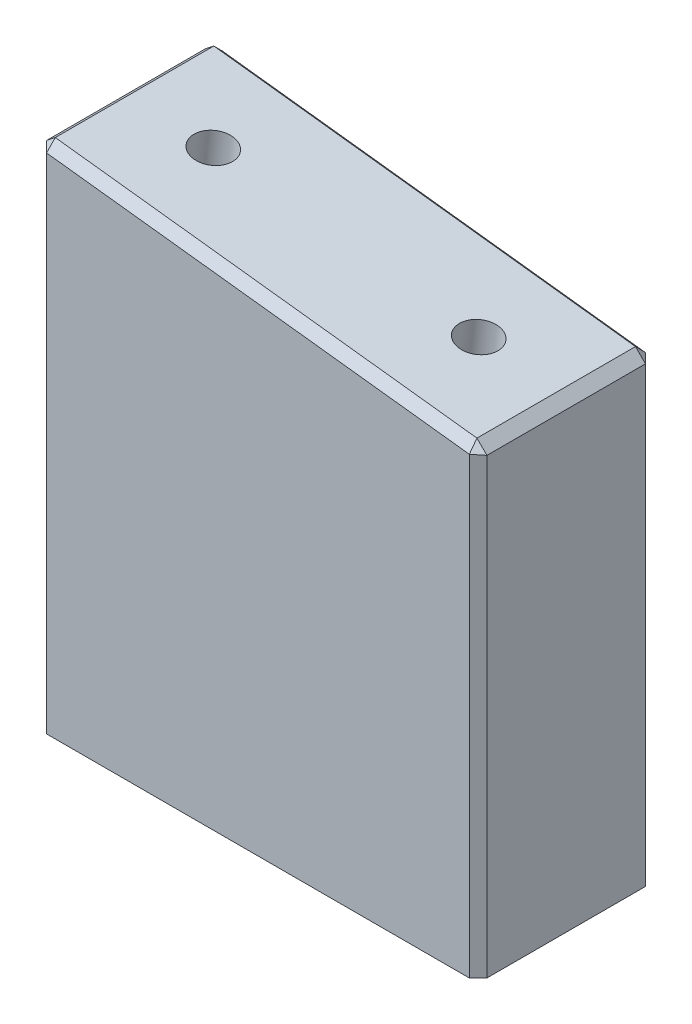
SolidWorks part; units mm, degrees
ref_plane "Front Plane" through (0, 0, 0) normal (0, 0, 1) x (1, 0, 0)
ref_plane "Top Plane" through (0, 0, 0) normal (0, 1, 0) x (1, 0, 0)
ref_plane "Right Plane" through (0, 0, 0) normal (1, 0, 0) x (0, 0, -1)
sketch "Sketch1" plane through (0, 0, 0) normal (0, 0, 1) x (1, 0, 0)
  line L0 (0, 0) -> (0, 80) construction
  line L1 (0, 80) -> (0, 85) construction
  line L2 (0, 85) -> (0, 90) construction
  line L3 (0, 90) -> (0, 95) construction
  line L4 (0, 58.252) -> (4.3106, 95) construction
  line L5 (4.3106, 95) -> (500.9058, 36.748) construction
  line L6 (500.9058, 36.748) -> (496.5951, 0) construction
  line L7 (496.5951, 0) -> (0, 58.252) construction
  line L8 (0, 0) -> (496.5951, 0) construction
  line L9 (0, 58.252) -> (0, 0)
  line L10 (0, 0) -> (50, 0)
  line L11 (50, 0) -> (50, 52.3868)
  line L12 (50, 52.3868) -> (0, 58.252)
  dimension "D1" = 80
  dimension "D2" = 5
  dimension "D3" = 5
  dimension "D4" = 5
  dimension "D5" = 500
  dimension "D6" = 37
  dimension "D7" = 50
extrude "Boss-Extrude1" add sketch "Sketch1" along normal blind 20
ref_plane "Plane1" through (6.0413, 51.5022, 0) normal (0.1165, 0.9932, 0) x (0.9932, -0.1165, 0)
sketch "Sketch2" plane through (6.7404, 57.4613, 0) normal (0.1165, 0.9932, 0) x (0.9932, -0.1165, 0)
  line L0 (-6.7866, -10) -> (43.5562, -10) construction
  line L1 (-6.7866, -20) -> (-6.7866, 0) construction
  line L2 (43.5562, -20) -> (43.5562, 0) construction
  circle A0 centre (3.2134, -10) radius 2.2
  circle A1 centre (33.5562, -10) radius 2.2
  dimension "D1" = 4.4
  dimension "D2" = 10
  dimension "D3" = 10
sketch "Sketch3" plane through (6.0413, 51.5022, 0) normal (0.1165, 0.9932, 0) x (0.9932, -0.1165, 0)
  line L0 (43.5562, 0) -> (-6.7866, 0) construction
  line L1 (-2.7866, -3) -> (39.5562, -3)
  line L2 (-2.7866, -3) -> (-2.7866, -17)
  line L3 (-2.7866, -17) -> (39.5562, -17)
  line L4 (39.5562, -3) -> (39.5562, -17)
  line L5 (43.5562, -20) -> (-6.7866, -20) construction
  dimension "D1" = 6
  dimension "D2" = 6
  dimension "D3" = 3
  dimension "D4" = 3
extrude "Cut-Extrude1" cut sketch "Sketch3" against normal blind 10
sketch "Sketch4" plane through (0, 0, 3) normal (0, 0, 1) x (1, 0, 0)
  line L0 (2.1087, 41.8949) -> (2.1087, 0)
  line L1 (0, 0) -> (50, 0) construction
  line L2 (2.1087, 0) -> (44.1632, 0)
  line L3 (44.1632, 0) -> (44.1632, 36.9618)
  line L4 (2.1087, 41.8949) -> (44.1632, 36.9618)
  point P5 (0, 0)
  point P10 (0, 0)
extrude "Cut-Extrude2" cut sketch "Sketch4" along normal blind 14
extrude "Cut-Extrude3" cut sketch "Sketch2" against normal up to surface (6 mm away) up to face at (24.301, 49.3603, 10)
chamfer "Chamfer1" distance 1 angle 45 8 edges at (50, 52.3868, 10) (50, 26.1934, 0) (0, 29.126, 0) (25, 55.3194, 0) (0, 58.252, 10) (0, 29.126, 20) (50, 26.1934, 20) (25, 55.3194, 20)
